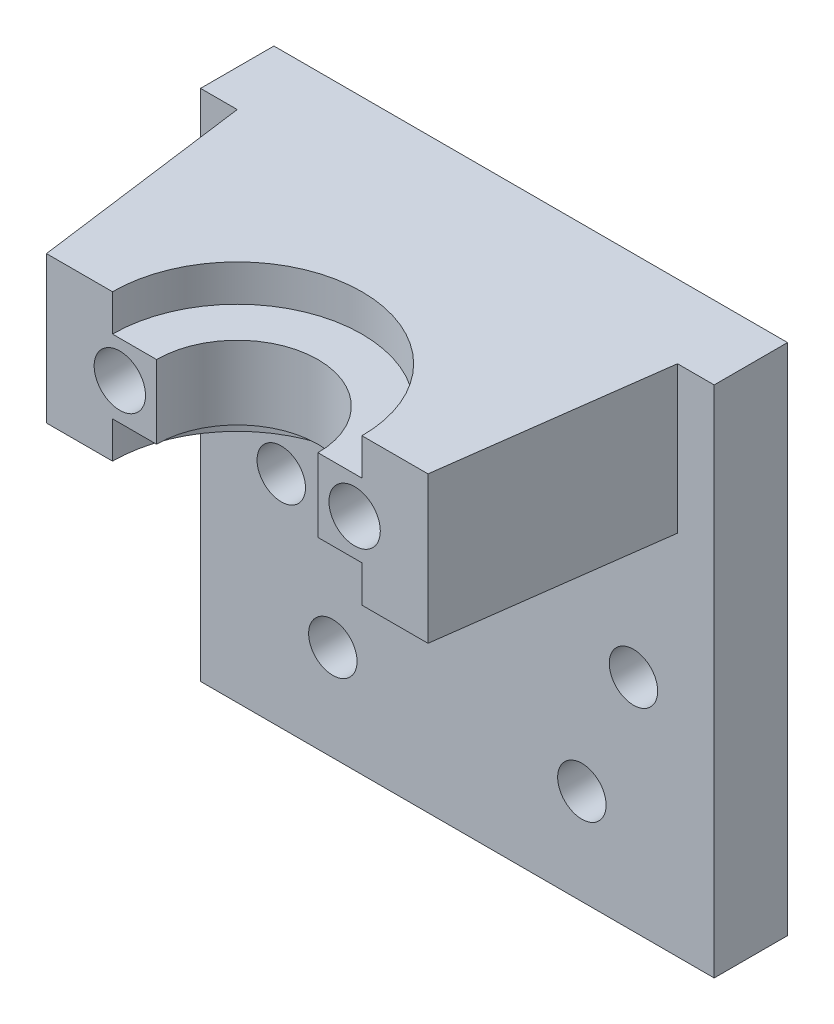
SolidWorks part; units mm, degrees
ref_plane "Plano frontal" through (0, 0, 0) normal (0, 0, 1) x (1, 0, 0)
ref_plane "Plano superior" through (0, 0, 0) normal (0, 1, 0) x (1, 0, 0)
ref_plane "Plano direito" through (0, 0, 0) normal (1, 0, 0) x (0, 0, -1)
sketch "Esboço1" plane through (0, 0, 0) normal (0, 0, 1) x (1, 0, 0)
  line L1 (-25, 25) -> (25, 25)
  line L2 (-25, 25) -> (-25, -25)
  line L3 (-25, -25) -> (25, -25)
  line L4 (25, 25) -> (25, -25)
  line L5 (-25, 25) -> (25, -25) construction
  line L6 (-25, -25) -> (25, 25) construction
  circle A0 centre (12, 0) radius 1.65
  circle A1 centre (8.4853, -8.4853) radius 1.65
  circle A3 centre (-8.4853, -8.4853) radius 1.65
  circle A4 centre (-12, 0) radius 1.65
  circle A5 centre (-8.4853, 8.4853) radius 1.65
  circle A7 centre (8.4853, 8.4853) radius 1.65
  circle A13 centre (0, 12) radius 1.65 [skipped]
  circle A14 centre (0, -12) radius 1.65 [skipped]
  point P0 (0, 0)
  point P24 (0, 0)
  point P25 (0, 0)
  dimension "D3" = 3.3
  dimension "D1" = 50
  dimension "D2" = 50
  dimension "D4" = 12
  dimension "D5" = 8
extrude "Ressalto-extrusão1" add sketch "Esboço1" along normal blind 5
sketch "Esboço2" plane through (0, 0, 0) normal (0, 1, 0) x (1, 0, 0)
  line L0 (13, -20) -> (15, -5)
  line L1 (25, -5) -> (-25, -5) construction
  line L2 (15, -5) -> (-15, -5)
  line L3 (-15, -5) -> (-13, -20)
  line L4 (-13, -20) -> (-5.5, -20)
  line L5 (5.5, -20) -> (13, -20)
  arc A0 (5.5, -20) -> (-5.5, -20) centre (0, -20) ccw
  point P10 (0, -5)
  dimension "D2" = 5.5
  dimension "D1" = 26
  dimension "D3" = 15
  dimension "D4" = 30
extrude "Ressalto-extrusão2" add sketch "Esboço2" along normal mid plane 10 from offset 15
sketch "Esboço4" plane through (0, 0, 0) normal (1, 0, 0) x (0, 0, -1)
  line L0 (-20, 20) -> (-11.5, 20)
  line L1 (-20, 20) -> (-5, 20) construction
  line L2 (-11.5, 20) -> (-11.5, 17.5)
  line L3 (-11.5, 17.5) -> (-20, 17.5)
  line L4 (-20, 20) -> (-20, 10) construction
  line L5 (-20, 17.5) -> (-20, 20)
  line L6 (-20, 15) -> (-23.0389, 15) construction
  line L7 (-20, 12.5) -> (-20, 10)
  line L8 (-11.5, 12.5) -> (-20, 12.5)
  line L9 (-11.5, 10) -> (-11.5, 12.5)
  line L10 (-20, 10) -> (-11.5, 10)
  line L11 (-20, 20) -> (-20, -14.7203) construction
  dimension "D1" = 5
  dimension "D2" = 8.5
revolve "Corte-Revolução3" cut sketch "Esboço4" angle 360 about L11
sketch "Esboço5" plane through (0, 0, 5) normal (0, 0, 1) x (1, 0, 0)
  line L1 (-17.5, -15) -> (17.5, -15)
  line L2 (-17.5, -15) -> (-17.5, 20)
  line L3 (-17.5, 20) -> (17.5, 20)
  line L4 (17.5, -15) -> (17.5, 20)
  line L5 (-17.5, -15) -> (17.5, 20) construction
  line L6 (-17.5, 20) -> (17.5, -15) construction
  line L7 (15, 20) -> (-15, 20) construction
  line L9 (-25, 25) -> (25, 25)
  line L10 (-25, 25) -> (-25, -25)
  line L11 (-25, -25) -> (25, -25)
  line L12 (25, 25) -> (25, -25)
  point P0 (0, 2.5)
  dimension "D1" = 15
  dimension "D2" = 35
extrude "Corte-extrusão1" cut sketch "Esboço5" against normal through all both and the other way through all
sketch "Esboço6" plane through (0, 0, 20) normal (0, 0, 1) x (1, 0, 0)
  line L0 (0, 0) -> (0, 20.7373) construction
  line L1 (-5.5, 17.5) -> (-5.5, 12.5) construction
  circle A0 centre (-8, 15) radius 1.75
  circle A1 centre (8, 15) radius 1.75
  point P11 (-5.5, 15)
  dimension "D1" = 3.5
  dimension "D2" = 16
extrude "Corte-extrusão2" cut sketch "Esboço6" against normal through all
